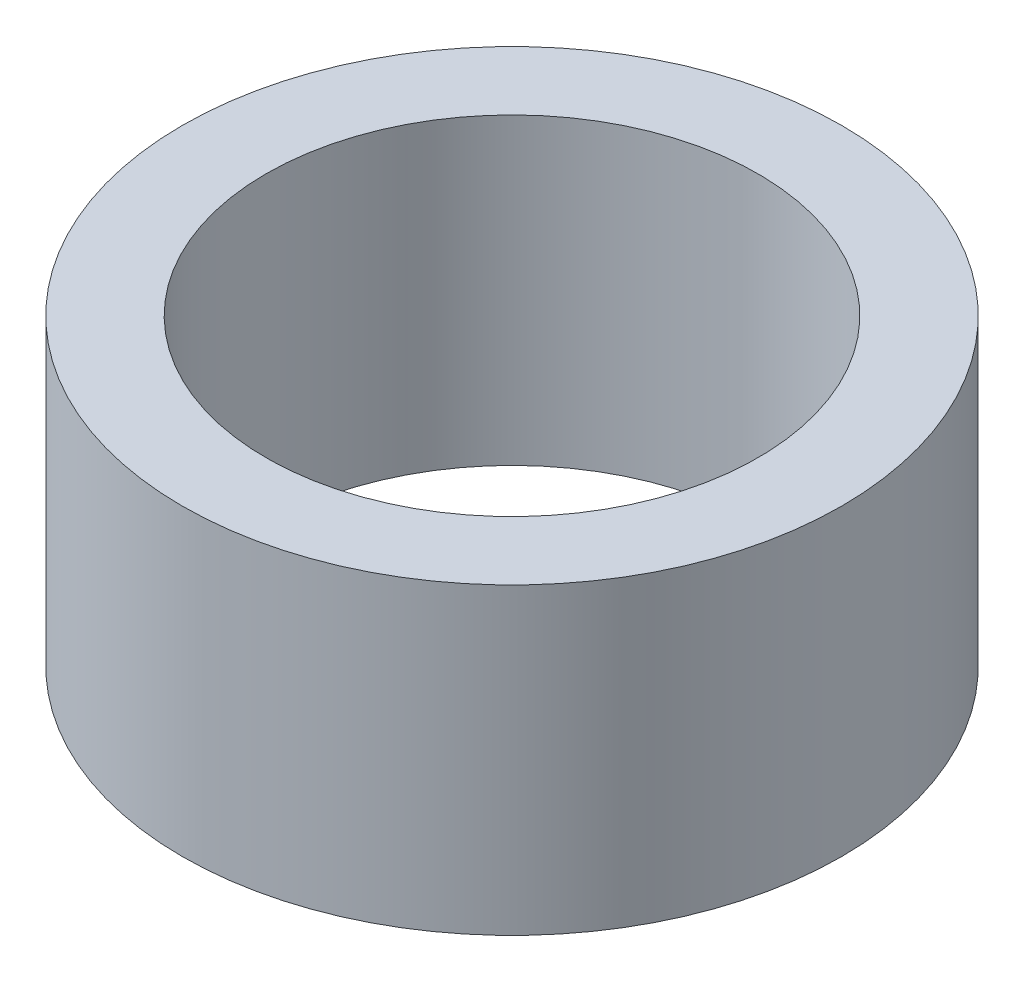
SolidWorks part; units mm, degrees
material "Laiton"
ref_plane "Plan de face" through (0, 0, 0) normal (0, 0, 1) x (1, 0, 0)
ref_plane "Plan de dessus" through (0, 0, 0) normal (0, 1, 0) x (1, 0, 0)
ref_plane "Plan de droite" through (0, 0, 0) normal (1, 0, 0) x (0, 0, -1)
sketch "Esquisse1" plane through (0, 0, 0) normal (0, 0, 1) x (1, 0, 0)
  line L0 (0, 208.6449) -> (0, 0) construction
  line L1 (4.7, 147.7497) -> (6.3, 147.7497)
  line L2 (4.7, 147.7497) -> (4.7, 153.5497)
  line L3 (4.7, 153.5497) -> (6.3, 153.5497)
  line L4 (6.3, 147.7497) -> (6.3, 153.5497)
  dimension "D1" = 6.3
  dimension "D2" = 5.8
  dimension "D3" = 4.7
revolve "Révolution1" add sketch "Esquisse1" angle 360 about L0
